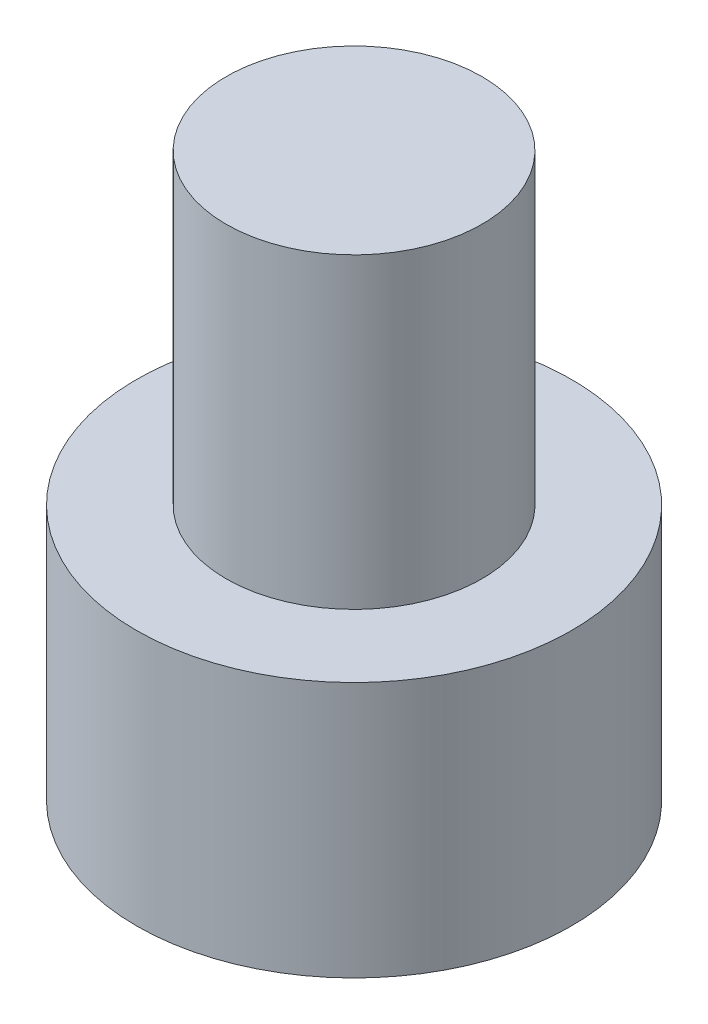
SolidWorks part; units mm, degrees
ref_plane "前视基准面" through (0, 0, 0) normal (0, 0, 1) x (1, 0, 0)
ref_plane "上视基准面" through (0, 0, 0) normal (0, 1, 0) x (1, 0, 0)
ref_plane "右视基准面" through (0, 0, 0) normal (1, 0, 0) x (0, 0, -1)
other "Configuration Table"
ref_plane "基准面2" through (0, 0, 0) normal (0, 0, -1) x (-1, 0, 0)
sketch "草图2" plane through (0, 0, 0) normal (0, 0, -1) x (-1, 0, 0)
  line L0 (-4.25, -5) -> (0, -5)
  line L1 (0, -5) -> (0, 0)
  line L2 (0, 0) -> (-4.25, 0)
  line L3 (-4.25, 0) -> (-4.25, -5)
  line L4 (0, -5) -> (0, 0) construction
  dimension "D1" = 4.25
  dimension "D2" = 5
revolve "旋转1" add sketch "草图2" angle 360 about L4
sketch "草图3" plane through (0, 0, 0) normal (0, 1, 0) x (-1, 0, 0)
  circle A0 centre (0, 0) radius 2.5
  dimension "D1" = 5
extrude "凸台-拉伸1" add sketch "草图3" along normal blind 6
sketch "草图4" plane through (0, -5, 0) normal (0, -1, 0) x (1, 0, 0)
  line L0 (-1.1547, -2) -> (1.1547, -2)
  line L1 (1.1547, -2) -> (2.3094, 0)
  line L2 (2.3094, 0) -> (1.1547, 2)
  line L3 (1.1547, 2) -> (-1.1547, 2)
  line L4 (-1.1547, 2) -> (-2.3094, 0)
  line L5 (-2.3094, 0) -> (-1.1547, -2)
  circle A0 centre (0, 0) radius 4.25 construction
  dimension "D1" = 1.1547
  dimension "D2" = 2.3094
  dimension "D3" = 1.1547
  dimension "D4" = 2.3094
  dimension "D5" = 2
  dimension "D6" = 2
extrude "切除-拉伸1" cut sketch "草图4" against normal blind 1
